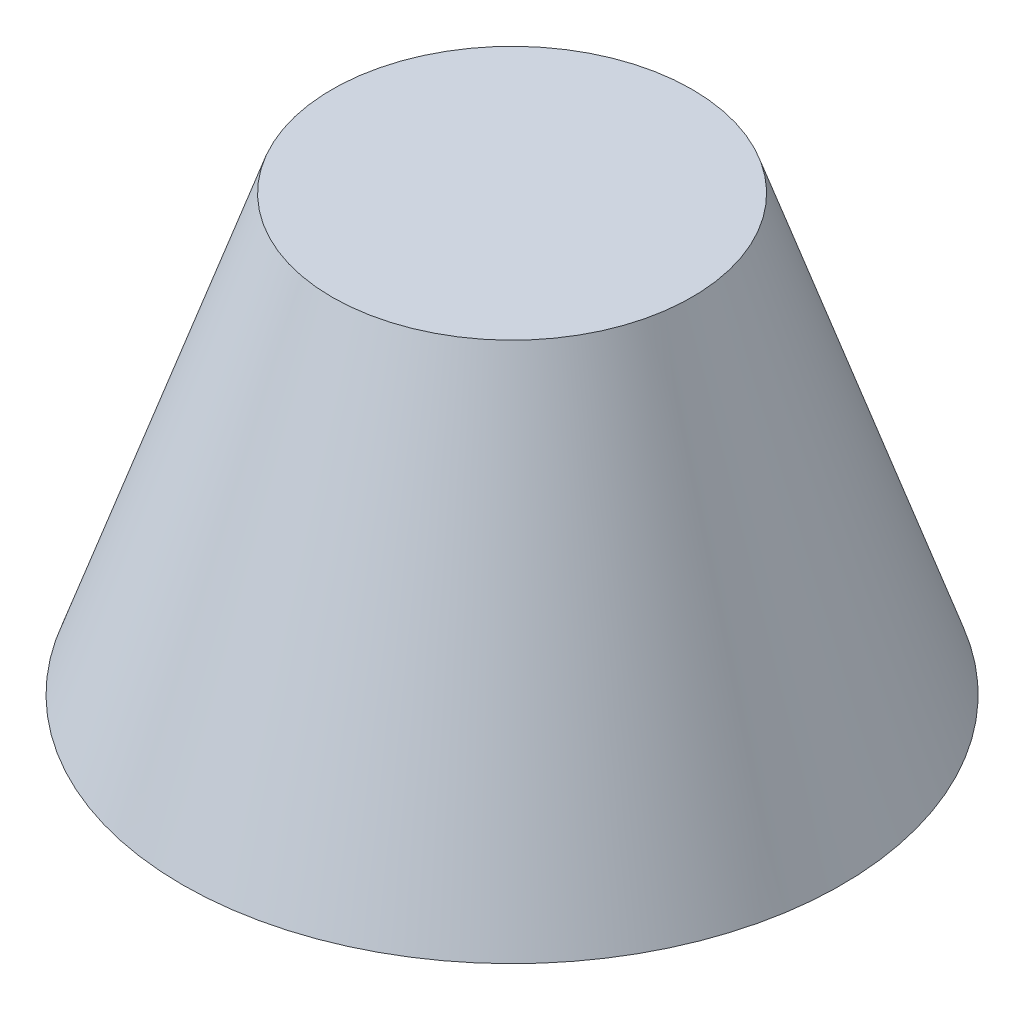
SolidWorks part; units mm, degrees
material "AISI 1020"
ref_plane "Front Plane" through (0, 0, 0) normal (0, 0, 1) x (1, 0, 0)
ref_plane "Top Plane" through (0, 0, 0) normal (0, 1, 0) x (1, 0, 0)
ref_plane "Right Plane" through (0, 0, 0) normal (1, 0, 0) x (0, 0, -1)
sketch "Sketch1" plane through (0, 0, 0) normal (0, 1, 0) x (1, 0, 0)
  circle A0 centre (0, 0) radius 68.3177
ref_plane "Plane1" through (0, 90, 0) normal (0, 1, 0) x (1, 0, 0)
sketch "Sketch2" plane through (0, 90, 0) normal (0, 1, 0) x (1, 0, 0)
  circle A0 centre (0, 0) radius 37.3125
loft "Loft1" add profiles "Sketch2", "Sketch1"
